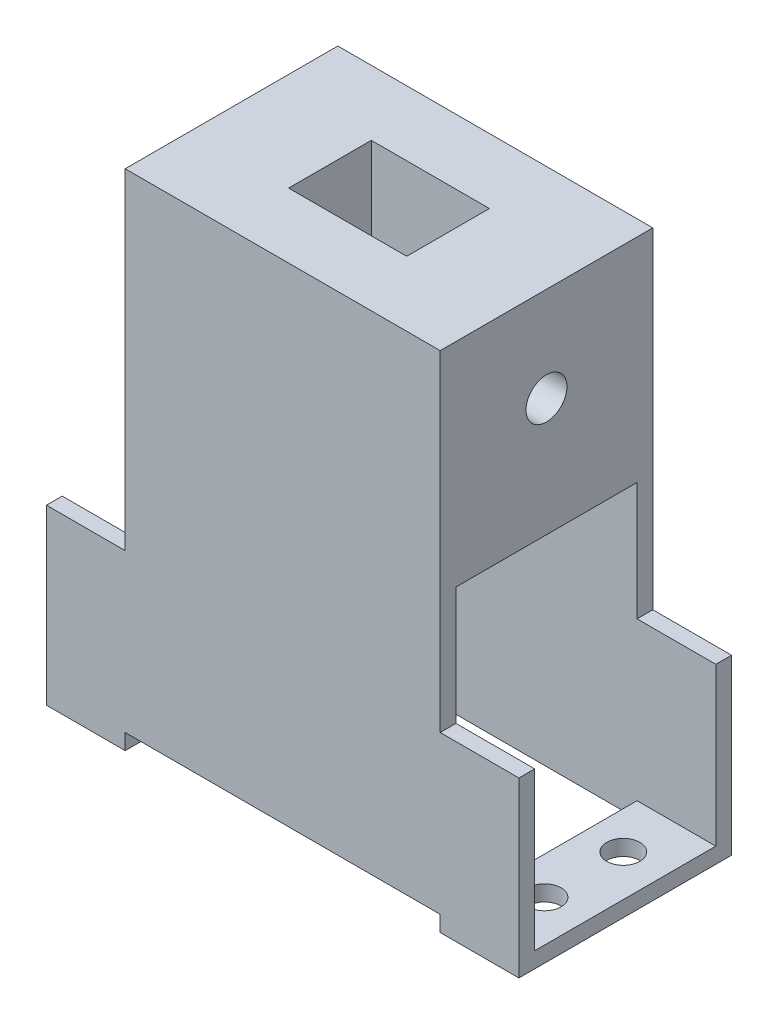
SolidWorks part; units mm, degrees
ref_plane "前视基准面" through (0, 0, 0) normal (0, 0, 1) x (1, 0, 0)
ref_plane "上视基准面" through (0, 0, 0) normal (0, 1, 0) x (1, 0, 0)
ref_plane "右视基准面" through (0, 0, 0) normal (1, 0, 0) x (0, 0, -1)
sketch "草图1" plane through (0, 0, 0) normal (0, 0, 1) x (1, 0, 0)
  line L0 (20, 2.5) -> (30, 2.5)
  line L1 (-20, -17.5) -> (20, -17.5)
  line L2 (-20, -17.5) -> (-20, 17.5)
  line L3 (-20, 17.5) -> (20, 17.5)
  line L4 (20, -17.5) -> (20, 17.5)
  line L5 (-20, -17.5) -> (20, 17.5) construction
  line L6 (-20, 17.5) -> (20, -17.5) construction
  line L7 (30, 2.5) -> (30, -17.5)
  line L8 (30, -17.5) -> (20, -17.5)
  line L9 (-20, -17.5) -> (-30, -17.5)
  line L10 (-30, -17.5) -> (-30, 2.5)
  line L11 (-30, 2.5) -> (-20, 2.5)
  line L12 (-30, -17.5) -> (-20, -17.5)
  point P0 (0, 0)
  dimension "D1" = 40
  dimension "D2" = 35
  dimension "D3" = 10
  dimension "D4" = 10
  dimension "D5" = 20
  dimension "D6" = 20
extrude "凸台-拉伸1" add sketch "草图1" along normal blind 2 contours L11 L10 L9 L2 | L1 L4 L3 L2 | L8 L7 L0 L4
sketch "草图3" plane through (0, -17.5, 0) normal (0, -1, 0) x (1, 0, 0)
  line L0 (-30, 2) -> (-30, -23)
  line L2 (-20, -23) -> (-20, 2)
  line L3 (30, 2) -> (-30, 2) construction
  line L4 (-20, 2) -> (-30, 2)
  line L5 (30, -23) -> (30, 2)
  line L6 (30, 2) -> (20, 2)
  line L7 (20, 2) -> (20, -23)
  line L10 (-30, -23) -> (-20, -23)
  line L11 (20, -23) -> (30, -23)
  dimension "D1" = 10
  dimension "D2" = 25
  dimension "D3" = 10
extrude "凸台-拉伸2" add sketch "草图3" along normal blind 2
sketch "草图4" plane through (0, 0, -23) normal (0, 0, -1) x (-1, 0, 0)
  line L0 (30, -19.5) -> (30, -17.5) construction
  line L1 (-30, -19.5) -> (-30, -17.5) construction
  line L2 (30, -19.5) -> (30, -17.5)
  line L3 (-30, -19.5) -> (-30, -17.5)
  line L4 (-30, -19.5) -> (30, -19.5)
  line L10 (30, 2.5) -> (20, 2.5)
  line L11 (20, 2.5) -> (20, 17.5)
  line L12 (20, 17.5) -> (-20, 17.5)
  line L13 (-20, 17.5) -> (-20, 2.5)
  line L14 (-20, 2.5) -> (-30, 2.5)
  line L15 (-30, 2.5) -> (-30, -17.5)
  line L16 (-30, -17.5) -> (-20, -17.5)
  line L17 (-20, -17.5) -> (20, -17.5)
  line L18 (20, -17.5) -> (30, -17.5)
  line L19 (30, -17.5) -> (30, 2.5)
  line L20 (30, 2.5) -> (20, 2.5)
  line L21 (20, 2.5) -> (20, 17.5)
  line L22 (20, 17.5) -> (-20, 17.5)
  line L23 (-20, 17.5) -> (-20, 2.5)
  line L24 (-20, 2.5) -> (-30, 2.5)
  line L25 (-30, 2.5) -> (-30, -17.5)
  line L29 (30, -17.5) -> (30, 2.5)
  dimension "D1" = 0
extrude "凸台-拉伸3" add sketch "草图4" along normal blind 2
sketch "草图5" plane through (0, -17.5, 0) normal (0, 1, 0) x (1, 0, 0)
  line L0 (20, 0) -> (20, 23) construction
  line L1 (20, -2) -> (20, 23) construction
  line L2 (-20, 23) -> (-20, -2) construction
  line L3 (30, 11.5) -> (-30, 11.5) construction
  line L4 (30, 23) -> (30, 0) construction
  line L5 (-30, 0) -> (-30, 23) construction
  circle A0 centre (24.75, 16.5) radius 2.1
  circle A1 centre (24.75, 6.5) radius 2.1
  circle A2 centre (-24.75, 16.5) radius 2.1
  circle A3 centre (-24.75, 6.5) radius 2.1
  dimension "D2" = 4.2
  dimension "D3" = 4.2
  dimension "D7" = 4.2
  dimension "D8" = 4.2
  dimension "D1" = 4.75
  dimension "D4" = 4.75
  dimension "D5" = 4.75
  dimension "D6" = 4.75
  dimension "D9" = 5
  dimension "D10" = 5
  dimension "D11" = 5
  dimension "D12" = 5
extrude "切除-拉伸1" cut sketch "草图5" against normal up to next
sketch "草图6" plane through (0, 17.5, 0) normal (0, 1, 0) x (1, 0, 0)
  line L1 (-20, 0) -> (-20, -2) construction
  line L2 (-20, -2) -> (20, -2) construction
  line L3 (20, -2) -> (20, 0) construction
  line L5 (20, 23) -> (20, 25) construction
  line L6 (20, 25) -> (-20, 25) construction
  line L7 (-20, 25) -> (-20, 23) construction
  line L9 (-20, 0) -> (-20, -2)
  line L10 (-20, -2) -> (20, -2)
  line L11 (20, -2) -> (20, 0)
  line L13 (20, 23) -> (20, 25)
  line L14 (20, 25) -> (-20, 25)
  line L15 (-20, 25) -> (-20, 23)
  line L16 (-20, 23) -> (-20, 0)
  line L17 (20, 23) -> (20, 0)
extrude "凸台-拉伸5" add sketch "草图6" along normal blind 2
sketch "草图7" plane through (0, 19.5, 0) normal (0, 1, 0) x (1, 0, 0)
  line L4 (20, -2) -> (20, 25)
  line L5 (20, 25) -> (-20, 25)
  line L6 (-20, 25) -> (-20, -2)
  line L7 (-20, -2) -> (20, -2)
  line L8 (20, -2) -> (20, 25)
  line L9 (20, 25) -> (-20, 25)
  line L10 (-20, 25) -> (-20, -2)
  line L11 (-20, -2) -> (20, -2)
  dimension "D1" = 0
extrude "凸台-拉伸6" add sketch "草图7" along normal blind 25
sketch "草图8" plane through (-20, 0, 0) normal (-1, 0, 0) x (0, 0, 1)
  line L0 (-11.5, 44.5) -> (-11.5, 17.5) construction
  line L1 (-25, 44.5) -> (2, 44.5) construction
  line L2 (-23, 17.5) -> (0, 17.5) construction
  circle A0 centre (-11.5, 32.5) radius 2.6
  dimension "D1" = 5.2
  dimension "D2" = 15
extrude "切除-拉伸2" cut sketch "草图8" against normal up to next
sketch "草图9" plane through (0, 44.5, 0) normal (0, 1, 0) x (1, 0, 0)
  line L0 (-20, 11.5) -> (20, 11.5) construction
  line L1 (-7.5, 6.25) -> (7.5, 6.25)
  line L2 (-7.5, 6.25) -> (-7.5, 16.75)
  line L3 (-7.5, 16.75) -> (7.5, 16.75)
  line L4 (7.5, 6.25) -> (7.5, 16.75)
  line L5 (-7.5, 6.25) -> (7.5, 16.75) construction
  line L6 (-7.5, 16.75) -> (7.5, 6.25) construction
  line L7 (-20, 25) -> (-20, -2) construction
  line L8 (20, -2) -> (20, 25) construction
  line L9 (0, -2) -> (0, 25) construction
  line L10 (-20, -2) -> (20, -2) construction
  line L11 (20, 25) -> (-20, 25) construction
  point P0 (0, 11.5)
  dimension "D1" = 10.5
  dimension "D2" = 15
extrude "切除-拉伸3" cut sketch "草图9" against normal blind 22.2
